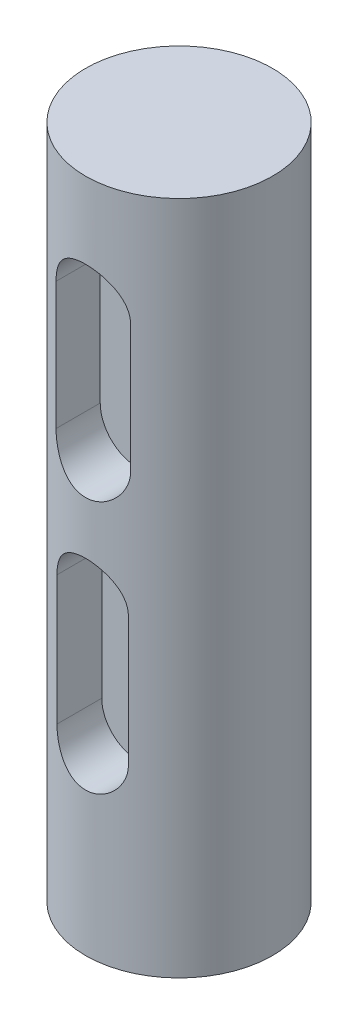
SolidWorks part; units mm, degrees
ref_plane "前视基准面" through (0, 0, 0) normal (0, 0, 1) x (1, 0, 0)
ref_plane "上视基准面" through (0, 0, 0) normal (0, 1, 0) x (1, 0, 0)
ref_plane "右视基准面" through (0, 0, 0) normal (1, 0, 0) x (0, 0, -1)
other "Configuration Table"
sketch "草图1" plane through (0, 0, 0) normal (0, 1, 0) x (1, 0, 0)
  circle A0 centre (0, 0) radius 9
  dimension "D1" = 18
ref_plane "基准面2" through (0, 10, 0) normal (0, 1, 0) x (1, 0, 0)
sketch "草图2" plane through (0, 10, 0) normal (0, 1, 0) x (1, 0, 0)
  circle A0 centre (0, 0) radius 9 construction
  circle A1 centre (0, 0) radius 9
extrude "凸台-拉伸1" add sketch "草图2" along normal blind 65
sketch "草图4" plane through (0, 0, 0) normal (0, 0, 1) x (1, 0, 0)
  line L0 (0, 27.2484) -> (0, 39.6968) construction
  line L1 (-3.4416, 27.2484) -> (-3.4416, 39.6968)
  line L2 (3.4416, 27.2484) -> (3.4416, 39.6968)
  arc A0 (-3.4416, 27.2484) -> (3.4416, 27.2484) centre (0, 27.2484) ccw
  arc A1 (3.4416, 39.6968) -> (-3.4416, 39.6968) centre (0, 39.6968) ccw
  point P3 (0, 33.4726)
extrude "切除-拉伸1" cut sketch "草图4" against normal blind 5 from offset 9
ref_plane "基准面3" through (0, 0, 9) normal (0, 0, 1) x (1, 0, 0)
sketch "草图5" plane through (0, 0, 9) normal (0, 0, 1) x (1, 0, 0)
  line L0 (0, 51.7898) -> (0, 64.0693) construction
  line L1 (-3.5908, 51.7898) -> (-3.5908, 64.0693)
  line L2 (3.5908, 51.7898) -> (3.5908, 64.0693)
  arc A0 (-3.5908, 51.7898) -> (3.5908, 51.7898) centre (0, 51.7898) ccw
  arc A1 (3.5908, 64.0693) -> (-3.5908, 64.0693) centre (0, 64.0693) ccw
  point P3 (0, 57.9295)
extrude "切除-拉伸2" cut sketch "草图5" against normal blind 5
